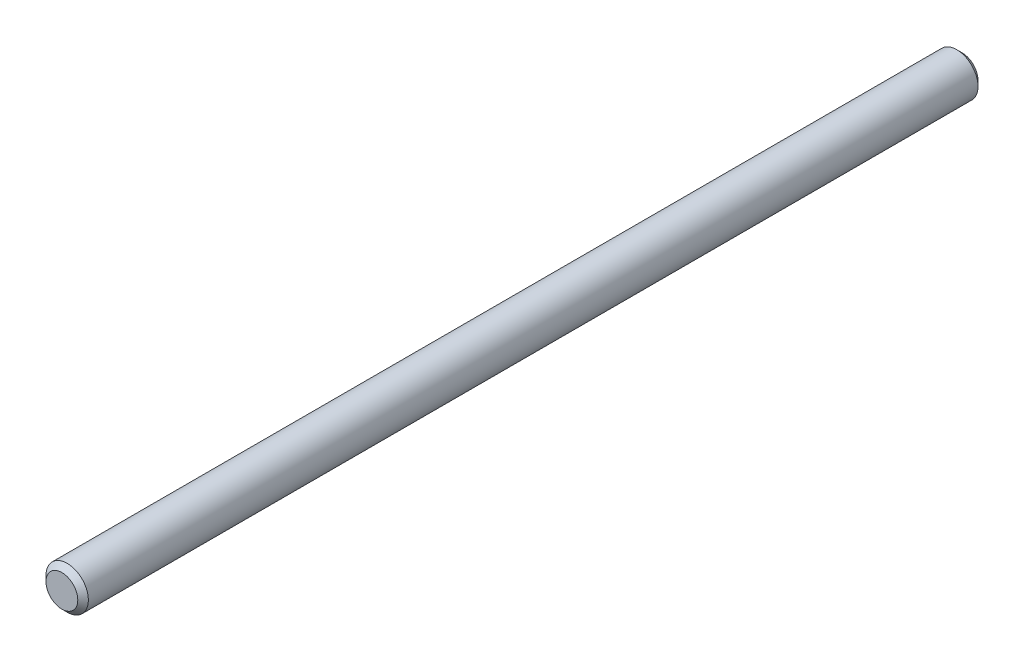
SolidWorks part; units mm, degrees
ref_plane "Plano frontal" through (0, 0, 0) normal (0, 0, 1) x (1, 0, 0)
ref_plane "Plano superior" through (0, 0, 0) normal (0, 1, 0) x (1, 0, 0)
ref_plane "Plano direito" through (0, 0, 0) normal (1, 0, 0) x (0, 0, -1)
sketch "Esboço1" plane through (0, 0, 0) normal (0, 0, 1) x (1, 0, 0)
  circle A0 centre (-40, -27) radius 4 construction
  circle A1 centre (-40, -27) radius 4
extrude "Ressalto-extrusão1" add sketch "Esboço1" along normal mid plane 170
chamfer "Chanfro1" distance 1 angle 45 2 edges at (-36, -27, -85) (-36, -27, 85)
